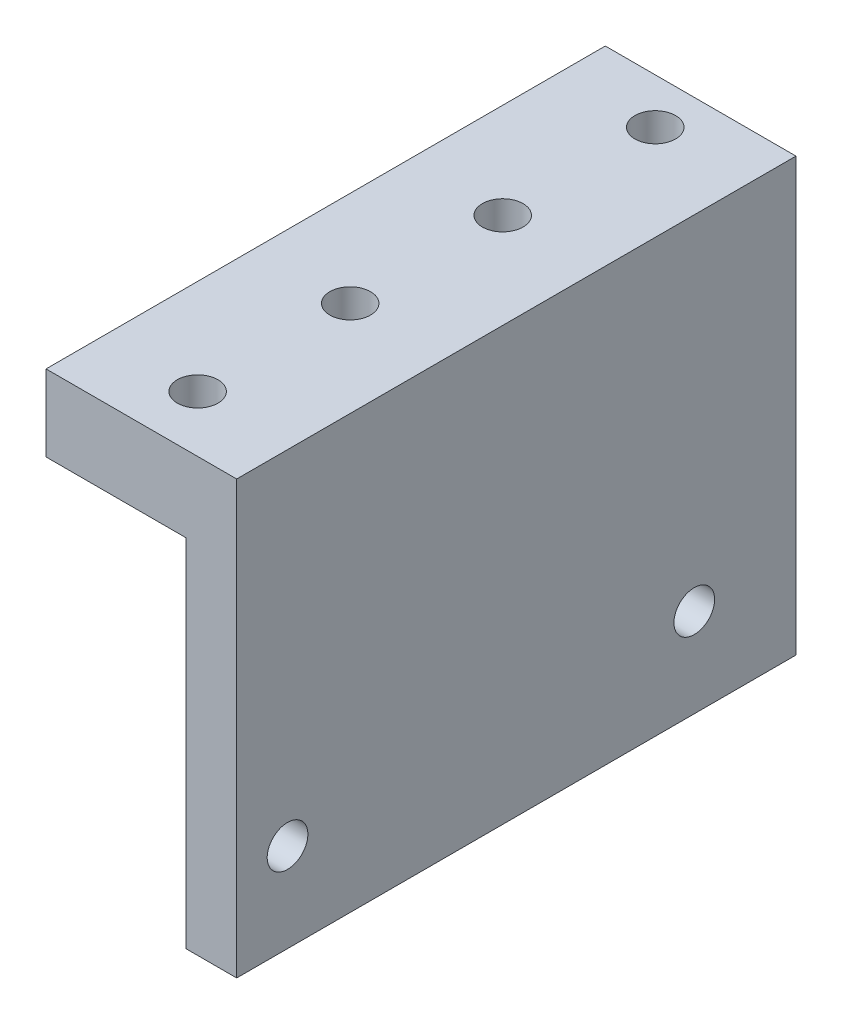
SolidWorks part; units mm, degrees
ref_plane "Front" through (0, 0, 0) normal (0, 0, 1) x (1, 0, 0)
ref_plane "Top" through (0, 0, 0) normal (0, 1, 0) x (1, 0, 0)
ref_plane "Right" through (0, 0, 0) normal (1, 0, 0) x (0, 0, -1)
sketch "Sketch1" plane through (0, 0, 0) normal (0, 0, 1) x (1, 0, 0)
  line L9 (-80.5852, 60.7408) -> (-80.5852, 54.7408)
  line L10 (-80.5852, 54.7408) -> (-69.5852, 54.7408)
  line L11 (-69.5852, 54.7408) -> (-69.5852, 26.7408)
  line L12 (-65.5852, 26.7408) -> (-69.5852, 26.7408)
  line L13 (-65.5852, 26.7408) -> (-65.5852, 60.7408)
  line L14 (-65.5852, 60.7408) -> (-80.5852, 60.7408)
  dimension "D1" = 34
  dimension "D2" = 6
  dimension "D3" = 15
  dimension "D4" = 4
extrude "Boss-Extrude1" add sketch "Sketch1" along normal blind 44
sketch "Sketch2" plane through (0, 60.7408, 0) normal (0, 1, 0) x (1, 0, 0)
  line L0 (-80.5852, -16.7132) -> (-73.0852, -16.7132) construction
  line L1 (-80.5852, -44) -> (-80.5852, 0) construction
  line L2 (-73.0852, -44) -> (-73.0852, -16.7132) construction
  line L6 (-65.5852, -44) -> (-80.5852, -44) construction
  line L7 (-73.0852, 0) -> (-73.0852, -16.7132) construction
  line L11 (-65.5852, 0) -> (-80.5852, 0) construction
  circle A0 centre (-73.0852, -3.5717) radius 1.6
  circle A1 centre (-73.0852, -15.5717) radius 1.6
  circle A2 centre (-73.0852, -27.5717) radius 1.6
  circle A3 centre (-73.0852, -39.5717) radius 1.6
  dimension "D2" = 3.2
  dimension "D1" = 7.5
  dimension "D3" = 4
sketch "Sketch3" plane through (-65.5852, 0, 0) normal (1, 0, 0) x (0, 0, -1)
  line L0 (-40, 26.7408) -> (-40, 33.7408) construction
  line L1 (-44, 26.7408) -> (0, 26.7408) construction
  line L2 (-44, 26.7408) -> (-44, 60.7408) construction
  circle A0 centre (-40, 33.7408) radius 1.6
  circle A1 centre (-8, 33.7408) radius 1.6
  dimension "D3" = 3.2
  dimension "D1" = 4
  dimension "D2" = 7
  dimension "D4" = 2
extrude "Cut-Extrude2" cut sketch "Sketch3" against normal blind 10
extrude "Cut-Extrude3" cut sketch "Sketch2" against normal blind 10
